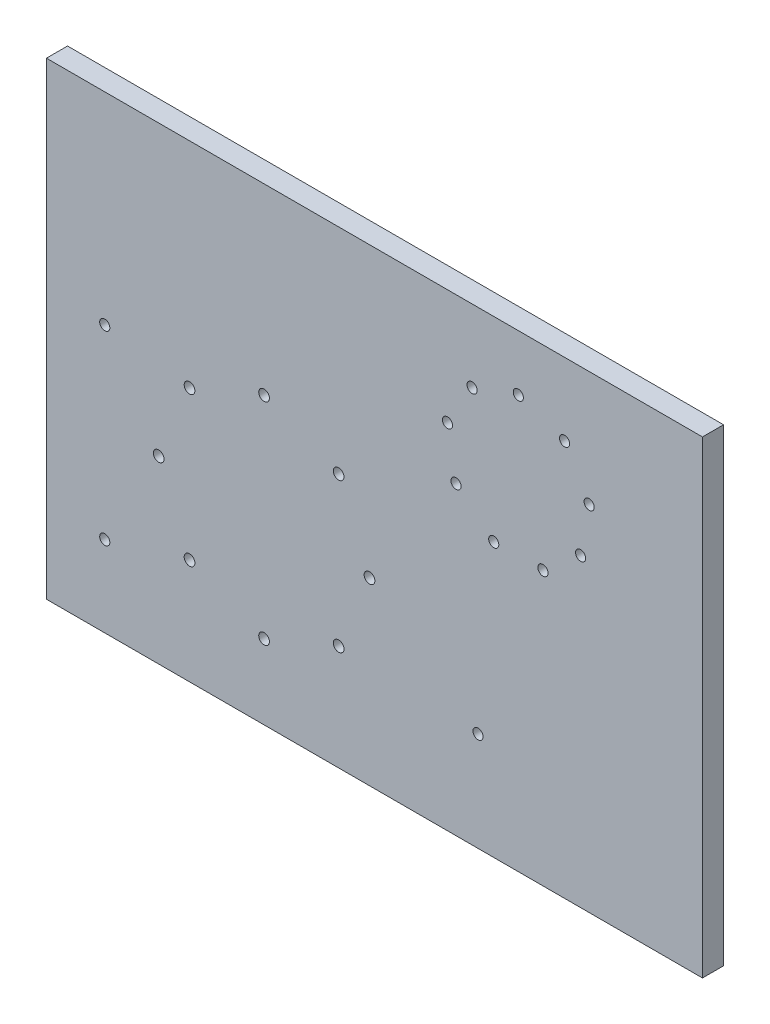
SolidWorks part; units mm, degrees
material "6061-T6 (SS)"
ref_plane "X-Y Datum" through (0, 0, 0) normal (0, 0, 1) x (1, 0, 0)
ref_plane "X-Z Datum" through (0, 0, 0) normal (0, 1, 0) x (1, 0, 0)
ref_plane "Y-Z Datum" through (0, 0, 0) normal (1, 0, 0) x (0, 0, -1)
sketch "Sketch1" plane through (0, 0, 0) normal (0, 0, 1) x (1, 0, 0)
  line L0 (1271.8081, 203.0591) -> (1124.4597, 266.6498)
  line L1 (0, 0) -> (355.6, 0)
  line L2 (0, 0) -> (0, 254)
  line L3 (0, 254) -> (355.6, 254)
  line L4 (355.6, 0) -> (355.6, 254)
  line L5 (1320.4443, 247.8927) -> (1278.6162, 371.5811)
  line L6 (1155.342, 396.316) -> (1261.26, 396.316) construction
  line L7 (1038.502, 396.316) -> (1155.342, 396.316) construction
  line L8 (1038.502, 253.0427) -> (1038.502, 396.316) construction
  line L9 (1038.502, 253.0427) -> (1148.992, 323.4946) construction
  line L10 (1148.992, 323.4946) -> (1286.152, 236.296) construction
  line L11 (1051.202, 383.616) -> (1148.992, 323.4946) construction
  line L12 (1148.992, 323.4946) -> (1268.4914, 368.1572) construction
  line L13 (1268.4474, 378.8452) -> (1181.6277, 378.4882)
  line L14 (1071.8207, 304.3899) -> (1054.4981, 282.4158)
  line L15 (1051.202, 265.7427) -> (1025.802, 265.7427) construction
  line L16 (1051.202, 265.7427) -> (1051.202, 240.3427) construction
  line L17 (1051.202, 240.3427) -> (1025.802, 240.3427) construction
  line L18 (1025.802, 265.7427) -> (1025.802, 240.3427) construction
  line L19 (1051.202, 265.7427) -> (1025.802, 240.3427) construction
  line L20 (1051.202, 240.3427) -> (1025.802, 265.7427) construction
  line L21 (1096.4557, 273.6277) -> (1063.8262, 267.175)
  line L22 (1064.0438, 387.8605) -> (1120.6311, 380.3201)
  line L23 (1053.1827, 372.2716) -> (1077.0766, 327.0647)
  line L24 (1051.202, 383.616) -> (1025.802, 383.616) construction
  line L25 (1051.202, 383.616) -> (1051.202, 409.016) construction
  line L26 (1051.202, 409.016) -> (1025.802, 409.016) construction
  line L27 (1025.802, 383.616) -> (1025.802, 409.016) construction
  line L28 (1051.202, 383.616) -> (1025.802, 409.016) construction
  line L29 (1051.202, 409.016) -> (1025.802, 383.616) construction
  line L30 (1038.502, 265.7427) -> (1051.202, 265.7427) construction
  line L31 (1038.502, 267.1672) -> (1038.502, 265.7427) construction
  line L32 (1055.7738, 283.746) -> (1039.8302, 270.058) construction
  line L33 (1056.8659, 257.9653) -> (1068.7052, 269.7756) construction
  line L34 (1051.202, 256.8527) -> (1054.1752, 256.8527) construction
  line L35 (1051.202, 265.7427) -> (1051.202, 256.8527) construction
  line L36 (1261.26, 396.316) -> (1261.26, 392.506) construction
  line L37 (1068.4045, 384.8426) -> (1055.8645, 394.3966) construction
  line L38 (1053.9403, 395.046) -> (1051.202, 395.046) construction
  line L39 (1051.202, 395.046) -> (1051.202, 383.616) construction
  line L40 (1051.202, 383.616) -> (1039.772, 383.616) construction
  line L41 (1039.772, 383.616) -> (1039.772, 381.6095) construction
  line L42 (1041.3211, 378.8825) -> (1057.7543, 369.0848) construction
  line L43 (117.969, 150.0126) -> (117.969, 159.5376) construction
  circle A8 centre (1062.632, 377.266) radius 10.6881 construction
  circle A37 centre (31.609, 144.5997) radius 3.3
  circle A38 centre (31.609, 43.8536) radius 3.3
  circle A39 centre (255.7818, 223.8236) radius 3.3
  circle A40 centre (255.7818, 184.8236) radius 18.6956
  circle A44 centre (233.919, 53.7454) radius 3.3
  circle A45 centre (1268.4914, 368.1572) radius 10.6881 construction
  circle A46 centre (1062.632, 377.266) radius 3.3 construction
  circle A47 centre (1268.4914, 368.1572) radius 3.3
  arc A48 (1268.4474, 378.8452) -> (1278.6162, 371.5811) centre (1268.4914, 368.1572) cw
  arc A49 (1271.8081, 203.0591) -> (1320.4443, 247.8927) centre (1286.152, 236.296) ccw
  circle A50 centre (1286.152, 236.296) radius 23.5
  circle A51 centre (1148.992, 323.4946) radius 61.9125 construction
  circle A52 centre (1148.992, 323.4946) radius 52.3875
  circle A53 centre (1286.152, 236.296) radius 36.2 construction
  arc A54 (1135.5887, 383.9388) -> (1174.1673, 380.0575) centre (1148.992, 323.4946) cw
  arc A55 (1096.4557, 273.6277) -> (1118.064, 269.8605) centre (1102.1072, 242.1888) cw
  circle A56 centre (1061.9783, 276.519) radius 3.3
  arc A57 (1181.6277, 378.4882) -> (1174.1673, 380.0575) centre (1181.553, 396.6512) cw
  circle A58 centre (1061.9783, 276.519) radius 3.3 construction
  arc A59 (1039.8302, 270.058) -> (1038.502, 267.1672) centre (1042.312, 267.1672) ccw construction
  arc A60 (1068.7052, 269.7756) -> (1055.7738, 283.746) centre (1061.9783, 276.519) ccw construction
  arc A61 (1054.1752, 256.8527) -> (1056.8659, 257.9653) centre (1054.1752, 260.6627) ccw construction
  circle A62 centre (1061.9783, 276.519) radius 9.525 construction
  arc A63 (1124.4597, 266.6498) -> (1118.064, 269.8605) centre (1148.992, 323.4946) cw
  arc A64 (1054.4981, 282.4158) -> (1063.8262, 267.175) centre (1061.9783, 276.519) ccw
  circle A65 centre (1062.632, 377.266) radius 3.3
  circle A66 centre (1122.049, 390.9612) radius 10.7351 construction
  arc A67 (1135.5887, 383.9388) -> (1126.0303, 380.9917) centre (1148.992, 323.4946) ccw
  arc A68 (1055.8645, 394.3966) -> (1053.9403, 395.046) centre (1053.9403, 391.871) ccw construction
  arc A69 (1039.772, 381.6095) -> (1041.3211, 378.8825) centre (1042.947, 381.6095) ccw construction
  arc A70 (1057.7543, 369.0848) -> (1068.4045, 384.8426) centre (1062.632, 377.266) ccw construction
  arc A71 (1077.0766, 327.0647) -> (1071.8207, 304.3899) centre (1050.3545, 321.3122) cw
  arc A72 (1064.0438, 387.8605) -> (1053.1827, 372.2716) centre (1062.632, 377.266) ccw
  arc A73 (1126.0303, 380.9917) -> (1120.6311, 380.3201) centre (1122.049, 390.9612) cw
  circle A74 centre (1261.26, 392.506) radius 12.7 construction
  circle A78 centre (117.969, 97.6251) radius 52.3875 construction
  circle A79 centre (117.969, 97.6251) radius 61.9125 construction
  circle A81 centre (117.969, 154.7751) radius 2.5
  circle A82 centre (158.3802, 138.0363) radius 2.5
  circle A83 centre (175.119, 97.6251) radius 2.5
  circle A84 centre (158.3802, 57.214) radius 2.5
  circle A85 centre (117.969, 40.4751) radius 2.5
  circle A86 centre (77.5578, 57.214) radius 2.5
  circle A87 centre (60.819, 97.6251) radius 2.5
  circle A88 centre (77.5578, 138.0363) radius 2.5
  circle A89 centre (255.7818, 184.8236) radius 18.6956
  circle A90 centre (280.8505, 214.6994) radius 3.3
  circle A91 centre (255.7818, 184.8236) radius 18.6956
  circle A92 centre (294.1893, 191.5959) radius 3.3
  circle A93 centre (255.7818, 184.8236) radius 18.6956
  circle A94 centre (289.5568, 165.3236) radius 3.3
  circle A95 centre (255.7818, 184.8236) radius 18.6956
  circle A96 centre (269.1206, 148.1756) radius 3.3
  circle A97 centre (255.7818, 184.8236) radius 18.6956
  circle A98 centre (242.443, 148.1756) radius 3.3
  circle A99 centre (255.7818, 184.8236) radius 18.6956
  circle A100 centre (222.0068, 165.3236) radius 3.3
  circle A101 centre (255.7818, 184.8236) radius 18.6956
  circle A102 centre (217.3743, 191.5959) radius 3.3
  circle A103 centre (255.7818, 184.8236) radius 18.6956
  circle A104 centre (230.7131, 214.6994) radius 3.3
  point P117 (255.7818, 184.8236)
  point P130 (117.969, 97.6251)
  point P149 (255.7818, 184.8236)
  dimension "D1" = 6.6
  dimension "D9" = 100.747
  dimension "D7" = 37.3912
  dimension "D19" = 104.775
  dimension "D20" = 104.775
  dimension "D21" = 123.825
  dimension "D22" = 123.825
  dimension "D23" = 5
  dimension "D2" = 355.6
  dimension "D3" = 31.609
  dimension "D4" = 100.7461
  dimension "D5" = 43.8536
  dimension "D6" = 224.1728
  dimension "D8" = 79.2239
  dimension "D10" = 9.1089
  dimension "D11" = 40.2239
  dimension "D13" = 86.36
  dimension "D14" = 9.8917
  dimension "D15" = 53.7715
  dimension "D16" = 202.31
  dimension "D17" = 53.7715
  dimension "D18" = 86.36
  dimension "D24" = 8
  dimension "D12" = 9
extrude "Boss-Extrude1" add sketch "Sketch1" along normal blind 11.43 contours L2 L1 L4 L3
hole_wizard "CBORE for M5 Hex Head Bolt1" positions "Sketch2" profile "Sketch3" counterbore size "M5" standard "ANSI Metric" end condition through all
sketch "Sketch2" plane through (0, 0, 0) normal (0, 0, -1) x (-1, 0, 0)
  point P0 (-158.3802, 138.0363)
  point P3 (-117.969, 154.7751)
  point P6 (-77.5578, 138.0363)
  point P9 (-60.819, 97.6251)
  point P12 (-77.5578, 57.214)
  point P15 (-117.969, 40.4751)
  point P18 (-158.3802, 57.214)
  point P21 (-175.119, 97.6251)
sketch "Sketch3" plane through (158.3802, 138.0363, 0) normal (1, 0, 0) x (0, 1, 0)
  line L0 (0, 0) -> (0, 11.43)
  line L1 (0, 11.43) -> (2.9, 11.43)
  line L3 (2.9, 11.43) -> (2.9, 3.58)
  line L4 (2.9, 3.58) -> (6.12, 3.58)
  line L5 (6.12, 3.58) -> (6.12, 0)
  line L7 (6.12, 0) -> (0, 0)
  line L11 (0, -6.35) -> (0, 107.95) construction
  dimension "Thru Hole Dia." = 5.8
  dimension "Thru Hole Depth" = 11.43
  dimension "C'Bore Dia." = 12.24
  dimension "C'Bore Depth" = 3.58
hole_wizard "M5 Clearance Hole1" positions "Sketch4" profile "Sketch5" hole size "M5" standard "ANSI Metric" end condition through all
sketch "Sketch4" plane through (0, 0, 11.43) normal (0, 0, 1) x (1, 0, 0)
  point P0 (31.609, 43.8536)
  point P3 (31.609, 144.5997)
  point P6 (233.919, 53.7454)
  point P9 (255.7818, 223.8236)
  point P12 (280.8505, 214.6994)
  point P15 (294.1893, 191.5959)
  point P18 (289.5568, 165.3236)
  point P21 (269.1206, 148.1756)
  point P24 (242.443, 148.1756)
  point P27 (222.0068, 165.3236)
  point P30 (217.3743, 191.5959)
  point P33 (230.7131, 214.6994)
sketch "Sketch5" plane through (31.609, 43.8536, 11.43) normal (1, 0, 0) x (0, -1, 0)
  line L0 (0, 0) -> (0, 11.43)
  line L1 (0, 11.43) -> (2.75, 11.43)
  line L2 (2.75, 11.43) -> (2.75, 0)
  line L5 (2.75, 0) -> (0, 0)
  line L11 (0, -6.35) -> (0, 107.95) construction
  dimension "Thru Hole Dia." = 5.5
  dimension "Thru Hole Depth" = 11.43
